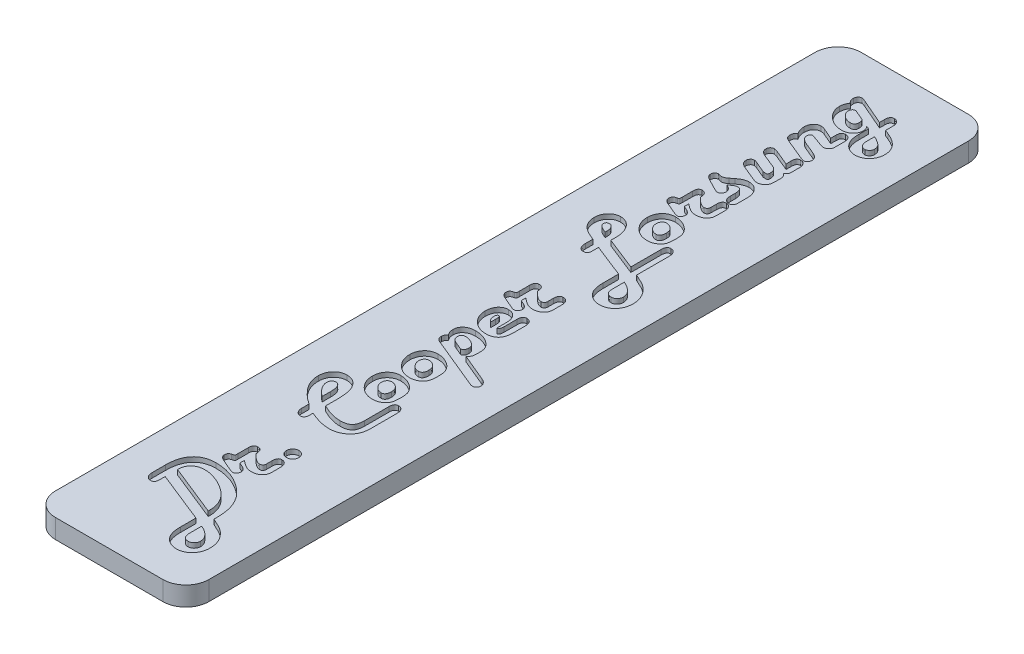
SolidWorks part; units mm, degrees
ref_plane "Front Plane" through (0, 0, 0) normal (0, 0, 1) x (1, 0, 0)
ref_plane "Top Plane" through (0, 0, 0) normal (0, 1, 0) x (1, 0, 0)
ref_plane "Right Plane" through (0, 0, 0) normal (1, 0, 0) x (0, 0, -1)
sketch "Sketch1" plane through (0, 0, 0) normal (0, 0, 1) x (1, 0, 0)
  line L0 (0, 1.5875) -> (0, -1.5875)
  line L1 (-12.7, 0) -> (12.7, 0) construction
  point P6 (0, 0)
  dimension "Width" = 25.4
  dimension "Thk" = 3.175
sketch "Sketch2" plane through (0, 0, 0) normal (1, 0, 0) x (0, 0, -1)
  line L0 (66.675, 0) -> (-66.675, 0)
  point P4 (0, 0)
  dimension "Length" = 133.35
sketch "Sketch3" plane through (0, 0, 0) normal (0, 0, 1) x (1, 0, 0)
  line L1 (12.7, 1.5875) -> (-12.7, 1.5875)
  line L2 (12.7, 1.5875) -> (12.7, -1.5875)
  line L3 (12.7, -1.5875) -> (-12.7, -1.5875)
  line L4 (-12.7, 1.5875) -> (-12.7, -1.5875)
  line L5 (12.7, 1.5875) -> (-12.7, -1.5875) construction
  line L6 (12.7, -1.5875) -> (-12.7, 1.5875) construction
  point P0 (0, 0)
extrude "Boss-Extrude1" add sketch "Sketch3" along normal up to vertex (66.675 mm away) and the other way up to vertex (66.675 mm away) up to point (0, 0, 66.675) other way up to point (0, 0, -66.675)
sketch "Sketch5" plane through (0, 1.5875, 0) normal (0, 1, 0) x (1, 0, 0)
  line L0 (-9.398, 66.929) -> (9.652, 66.929) construction
  line L1 (12.954, 63.627) -> (12.954, -63.373) construction
  line L2 (9.652, -66.675) -> (-9.398, -66.675) construction
  line L3 (-12.7, -63.373) -> (-12.7, 63.627) construction
  line L12 (12.7, -66.675) -> (12.7, 66.675)
  line L13 (12.7, 66.675) -> (-12.7, 66.675)
  line L14 (-12.7, 66.675) -> (-12.7, -66.675)
  line L15 (-12.7, -66.675) -> (12.7, -66.675)
  line L16 (12.7, -62.865) -> (12.7, 62.865)
  line L17 (8.89, 66.675) -> (-8.89, 66.675)
  line L18 (-12.7, 62.865) -> (-12.7, -62.865)
  line L19 (-8.89, -66.675) -> (8.89, -66.675)
  arc A0 (9.652, -66.675) -> (12.954, -63.373) centre (9.652, -63.373) ccw construction
  arc A1 (9.652, -66.675) -> (12.954, -63.373) centre (9.652, -63.373) ccw construction
  arc A2 (-12.7, -63.373) -> (-9.398, -66.675) centre (-9.398, -63.373) ccw construction
  arc A3 (-12.7, -63.373) -> (-9.398, -66.675) centre (-9.398, -63.373) ccw construction
  arc A4 (12.954, 63.627) -> (9.652, 66.929) centre (9.652, 63.627) ccw construction
  arc A5 (12.954, 63.627) -> (9.652, 66.929) centre (9.652, 63.627) ccw construction
  arc A6 (-9.398, 66.929) -> (-12.7, 63.627) centre (-9.398, 63.627) ccw construction
  arc A7 (-9.398, 66.929) -> (-12.7, 63.627) centre (-9.398, 63.627) ccw construction
  arc A8 (12.7, 62.865) -> (8.89, 66.675) centre (8.89, 62.865) ccw
  arc A9 (-8.89, 66.675) -> (-12.7, 62.865) centre (-8.89, 62.865) ccw
  arc A10 (12.7, -62.865) -> (8.89, -66.675) centre (8.89, -62.865) cw
  arc A11 (-8.89, -66.675) -> (-12.7, -62.865) centre (-8.89, -62.865) cw
  dimension "D2" = 3.81
  dimension "D1" = 0
extrude "Cut-Extrude2" cut sketch "Sketch5" against normal through all flip side to cut
sketch "Sketch4" plane through (0, 1.5875, 0) normal (0, 1, 0) x (1, 0, 0)
  line L0 (0, 0) -> (2.54, 0) construction
  line L1 (2.54, -66.675) -> (2.54, 66.675) construction
  line L2 (8.89, 66.675) -> (-8.89, 66.675) construction
  text T0 "Dr. Cooper Lorsung" font "Harlow Solid Italic" height 10
  point P8 (2.54, 0)
  dimension "D1" = 2.54
extrude "Cut-Extrude1" cut sketch "Sketch4" against normal blind 0.7937
